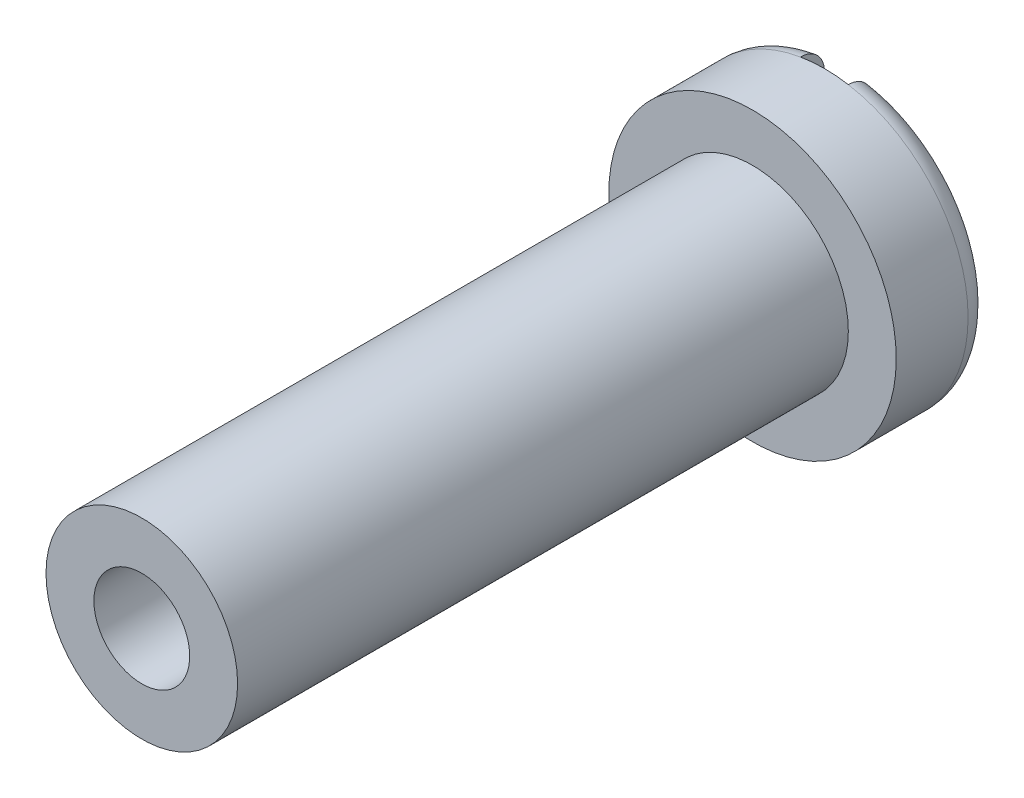
SolidWorks part; units mm, degrees
ref_plane "Front Plane" through (0, 0, 0) normal (0, 0, 1) x (1, 0, 0)
ref_plane "Top Plane" through (0, 0, 0) normal (0, 1, 0) x (1, 0, 0)
ref_plane "Right Plane" through (0, 0, 0) normal (1, 0, 0) x (0, 0, -1)
sketch "Sketch1" plane through (0, 0, 0) normal (0, 0, 1) x (1, 0, 0)
  circle A0 centre (0, 0) radius 3
  dimension "D1" = 6
extrude "Boss-Extrude1" add sketch "Sketch1" along normal blind 2
fillet "Fillet1" radius 0.5 1 edges at (3, 0, 0)
sketch "Sketch2" plane through (0, 0, 2) normal (0, 0, 1) x (1, 0, 0)
  circle A0 centre (0, 0) radius 2
  dimension "D1" = 4
extrude "Boss-Extrude2" add sketch "Sketch2" along normal blind 12.75
cosmetic thread "Cosmetic Thread2" parameters "D1"=4, "D2"=3.22
sketch "Sketch3" plane through (0, 0, 0) normal (0, 0, -1) x (-1, 0, 0)
  circle A0 centre (0, 0) radius 1
  dimension "D1" = 2
extrude "Cut-Extrude1" cut sketch "Sketch3" against normal through all both and the other way through all
ref_plane "Plane2" through (0, 0, 0) normal (0, 0, -1) x (-1, 0, 0)
sketch "Sketch4" plane through (0, 0, 0) normal (0, 0, -1) x (-1, 0, 0)
  line L1 (-0.5, -3) -> (0.5, -3)
  line L2 (-0.5, -3) -> (-0.5, 3)
  line L3 (-0.5, 3) -> (0.5, 3)
  line L4 (0.5, -3) -> (0.5, 3)
  line L5 (-0.5, -3) -> (0.5, 3) construction
  line L6 (-0.5, 3) -> (0.5, -3) construction
  point P0 (0, 0)
  dimension "D1" = 0.5
  dimension "D2" = 6
extrude "Cut-Extrude3" cut sketch "Sketch4" against normal blind 0.5
sketch "Sketch6" plane through (0, 0, 0) normal (0, 1, 0) x (1, 0, 0)
  line L0 (-2, -2) -> (-2, -14.75) construction
  line L1 (-2, -14.75) -> (2, -14.75) construction
  point P0 (-2, -10.75)
  point P5 (2, -10.75)
  point P6 (-2, -12.75)
  dimension "D1" = 4
  dimension "D2" = 2
